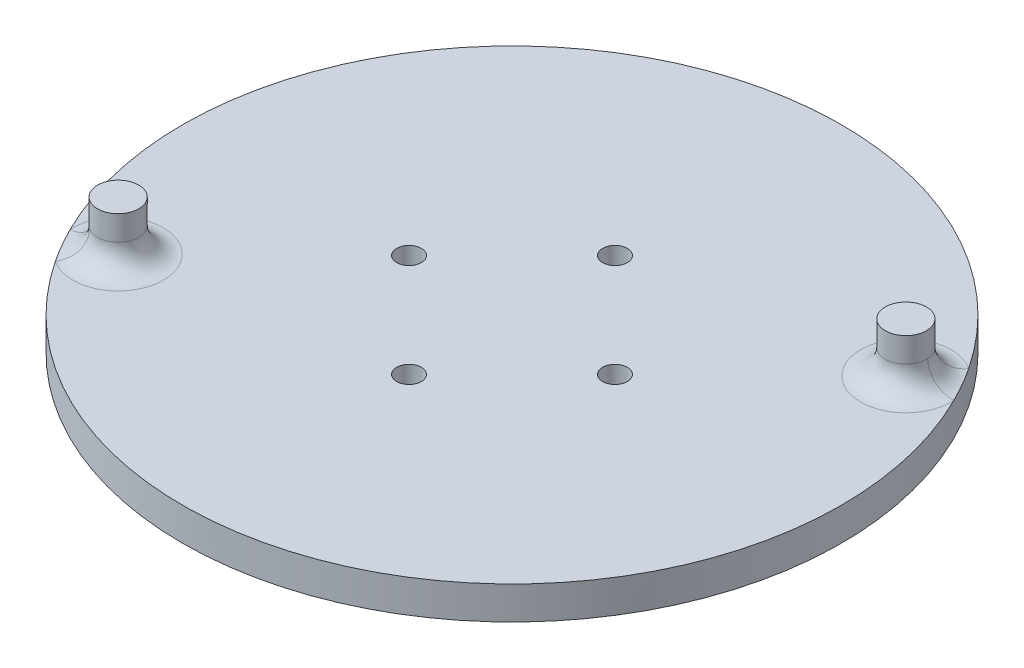
SolidWorks part; units mm, degrees
ref_plane "Front Plane" through (0, 0, 0) normal (0, 0, 1) x (1, 0, 0)
ref_plane "Top Plane" through (0, 0, 0) normal (0, 1, 0) x (1, 0, 0)
ref_plane "Right Plane" through (0, 0, 0) normal (1, 0, 0) x (0, 0, -1)
sketch "Sketch1" plane through (0, 0, 0) normal (0, 1, 0) x (1, 0, 0)
  line L0 (0, 0) -> (0, -12.5) construction
  circle A0 centre (0, 0) radius 40
  circle A5 centre (0, 0) radius 12.5 construction
  circle A6 centre (0, -12.5) radius 1.5
  circle A7 centre (-12.5, 0) radius 1.5
  circle A8 centre (0, 12.5) radius 1.5
  circle A9 centre (12.5, 0) radius 1.5
  point P15 (0, 0)
  dimension "D1" = 80
  dimension "D2" = 25
  dimension "D4" = 4
  dimension "D3" = 3
extrude "Boss-Extrude1" add sketch "Sketch1" along normal blind 4
sketch "Sketch2" plane through (0, 4, 0) normal (0, 1, 0) x (1, 0, 0)
  line L0 (0, 0) -> (0, -35) construction
  line L1 (0, 0) -> (30.3109, 17.5) construction
  line L2 (0, 0) -> (-30.3109, -17.5) construction
  circle A0 centre (0, 0) radius 29.5 construction
  circle A1 centre (0, 0) radius 35 construction
  circle A2 centre (30.3109, 17.5) radius 2.5
  circle A3 centre (-30.3109, -17.5) radius 2.5
  dimension "D1" = 59
  dimension "D2" = 70
  dimension "D4" = 5
  dimension "D5" = 60
  dimension "D6" = 5
  dimension "D3" = 180
extrude "Boss-Extrude2" add sketch "Sketch2" along normal blind 6
fillet "Fillet1" radius 3 2 edges at (30.3109, 4, -15) (-30.3109, 4, 20)
